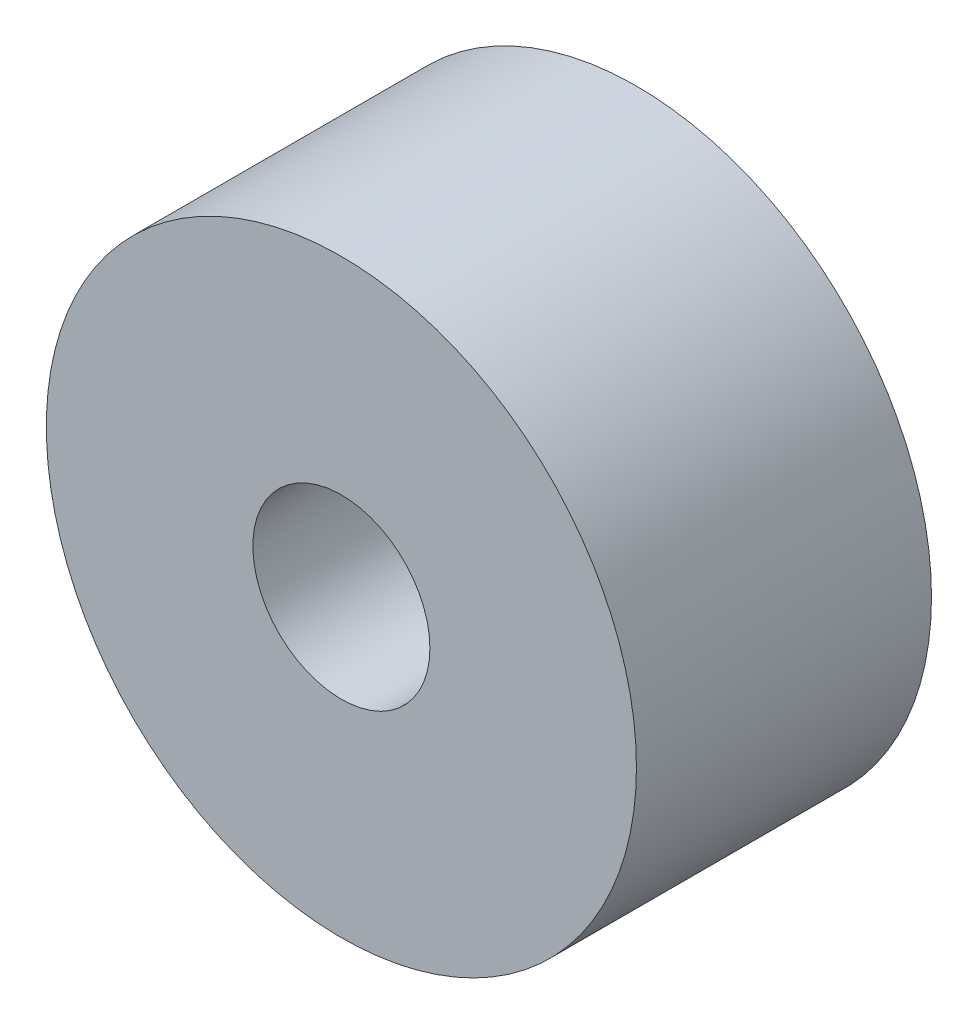
SolidWorks part; units mm, degrees
ref_plane "Alzado" through (0, 0, 0) normal (0, 0, 1) x (1, 0, 0)
ref_plane "Planta" through (0, 0, 0) normal (0, 1, 0) x (1, 0, 0)
ref_plane "Vista lateral" through (0, 0, 0) normal (1, 0, 0) x (0, 0, -1)
sketch "Croquis1" plane through (0, 0, 0) normal (0, 0, 1) x (1, 0, 0)
  circle A0 centre (0, 0) radius 2.5
  circle A1 centre (0, 0) radius 0.75
extrude "Saliente-Extruir1" add sketch "Croquis1" along normal blind 2.5
